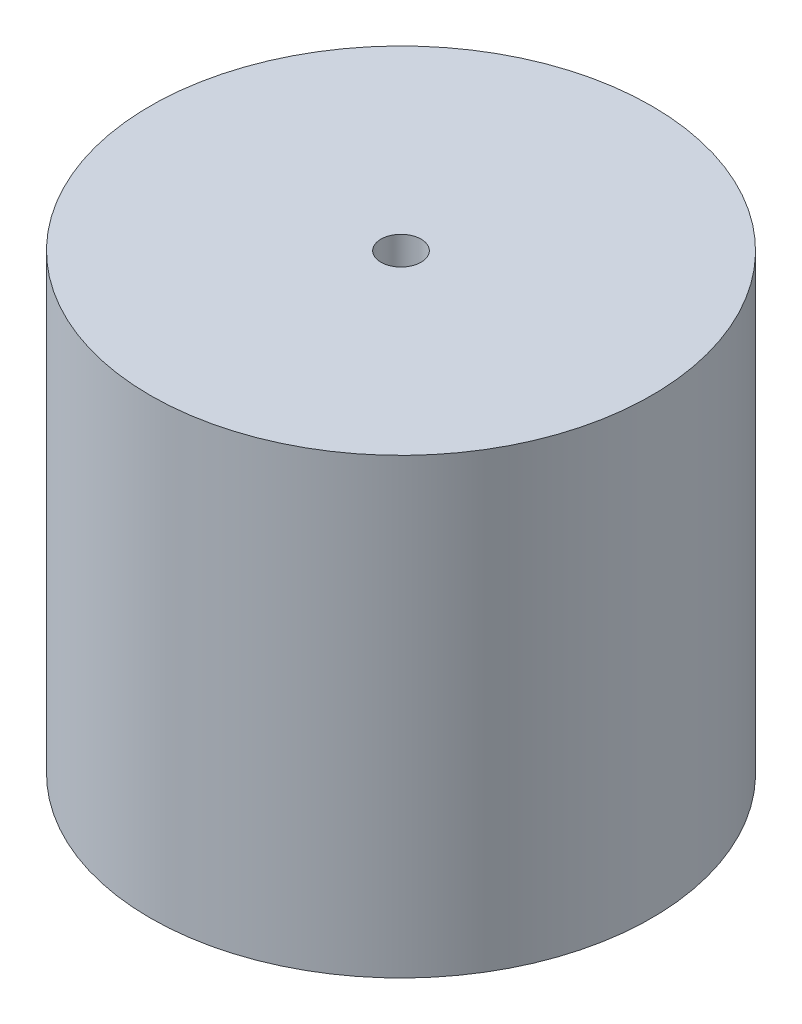
SolidWorks part; units mm, degrees
ref_plane "Front Plane" through (0, 0, 0) normal (0, 0, 1) x (1, 0, 0)
ref_plane "Top Plane" through (0, 0, 0) normal (0, 1, 0) x (1, 0, 0)
ref_plane "Right Plane" through (0, 0, 0) normal (1, 0, 0) x (0, 0, -1)
sketch "Sketch1" plane through (0, 0, 0) normal (0, 1, 0) x (1, 0, 0)
  circle A0 centre (0, 0) radius 75
  circle A1 centre (0, 0) radius 6
  dimension "D1" = 150
  dimension "D2" = 12
extrude "Boss-Extrude1" add sketch "Sketch1" along normal blind 135.4
sketch "Sketch3" plane through (0, 0, 0) normal (0, -1, 0) x (1, 0, 0)
  circle A0 centre (0, 0) radius 65
extrude "Cut-Extrude2" cut sketch "Sketch3" against normal blind 110
sketch "Sketch4" plane through (0, 0, 0) normal (0, -1, 0) x (1, 0, 0)
  circle A0 centre (0, 0) radius 75
  circle A1 centre (0, 0) radius 6
extrude "Boss-Extrude2" add sketch "Sketch4" against normal blind 10
